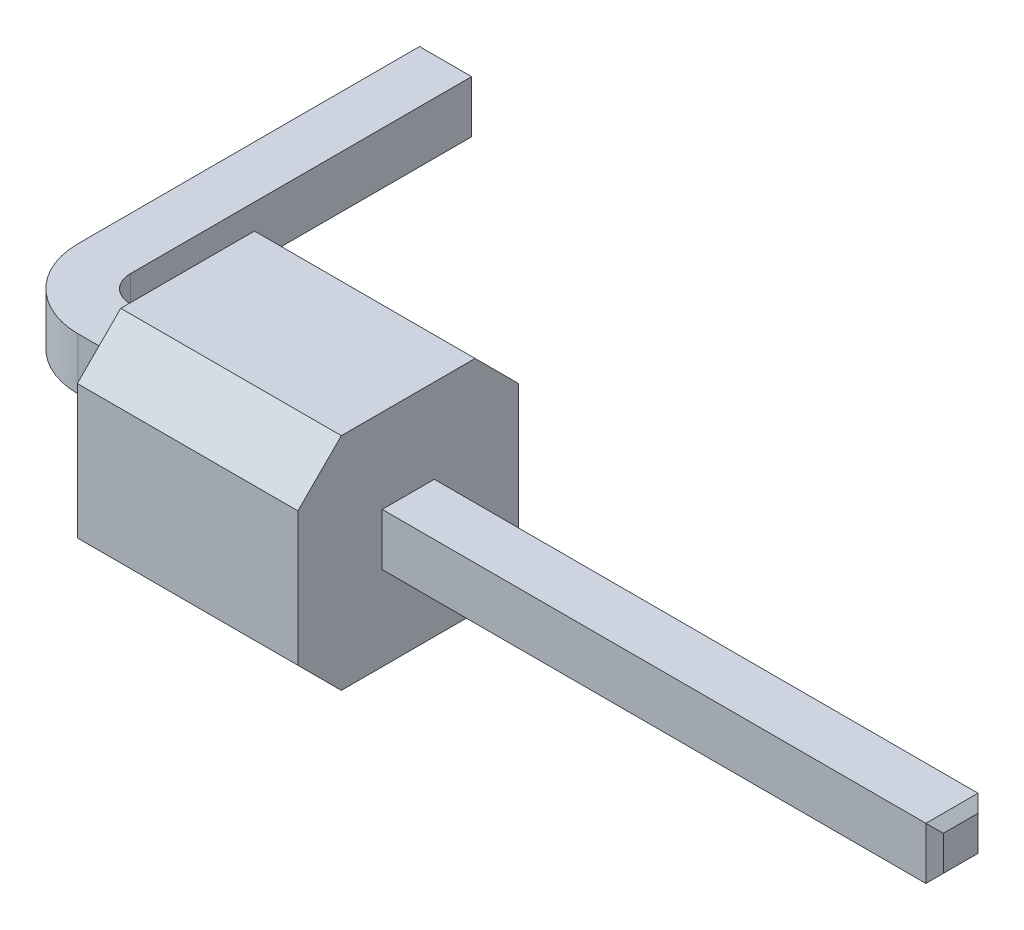
SolidWorks part; units mm, degrees
ref_plane "Front Plane" through (0, 0, 0) normal (0, 0, 1) x (1, 0, 0)
ref_plane "Top Plane" through (0, 0, 0) normal (0, 1, 0) x (1, 0, 0)
ref_plane "Right Plane" through (0, 0, 0) normal (1, 0, 0) x (0, 0, -1)
sketch "Sketch1" plane through (0, 0, 0) normal (1, 0, 0) x (0, 0, -1)
  line L0 (0, 0) -> (-1.27, 0) construction
  line L5 (-1.27, 0) -> (-1.27, 1.27) construction
  line L6 (-2.04, 1.27) -> (-0.5, 1.27)
  line L7 (-0.5, 1.27) -> (0, 0.77)
  line L8 (0, 0.77) -> (0, -0.77)
  line L9 (-2.54, 0.77) -> (-2.54, -0.77)
  line L10 (-2.04, 1.27) -> (-2.54, 0.77)
  line L11 (-0.5, -1.27) -> (0, -0.77)
  line L12 (-2.04, -1.27) -> (-0.5, -1.27)
  line L13 (-2.04, -1.27) -> (-2.54, -0.77)
  point P13 (-2.54, 0)
  dimension "D1" = 1.27
  dimension "D2" = 45
  dimension "D3" = 0.5
extrude "Plastic" add sketch "Sketch1" along normal blind 2.54
sketch "Sketch2" plane through (0, 0, 0) normal (0, 1, 0) x (1, 0, 0)
  line L0 (-1.56, 3.36) -> (-1.56, -0.67) construction
  line L1 (-0.96, -1.27) -> (8.9, -1.27) construction
  line L2 (0, -2.04) -> (0, -0.5) construction
  line L3 (-1.86, 3.36) -> (-1.86, -0.67)
  line L4 (-0.96, -1.57) -> (8.9, -1.57)
  line L5 (-1.26, 3.36) -> (-1.26, -0.67)
  line L6 (-0.96, -0.97) -> (8.9, -0.97)
  line L7 (-1.86, 3.36) -> (-1.26, 3.36)
  line L8 (8.9, -1.57) -> (8.9, -0.97)
  line L9 (2.54, -2.54) -> (0, -2.54) construction
  line L10 (2.54, -2.04) -> (2.54, -0.5) construction
  arc A0 (-1.56, -0.67) -> (-0.96, -1.27) centre (-0.96, -0.67) ccw construction
  arc A1 (-1.86, -0.67) -> (-0.96, -1.57) centre (-0.96, -0.67) ccw
  arc A2 (-1.26, -0.67) -> (-0.96, -0.97) centre (-0.96, -0.67) ccw
  point P5 (0, -1.27)
  dimension "D1" = 0.6
  dimension "D4" = 8.9
  dimension "D5" = 5.9
  dimension "D6" = 4.4
  dimension "D2" = 0.3
  dimension "D3" = 0.3
extrude "Contact" add sketch "Sketch2" along normal mid plane 0.6
chamfer "Chamfer1" distance 0.1 angle 45 8 edges at (8.9, 0.3, 1.27) (8.9, 0, 1.57) (8.9, -0.3, 1.27) (8.9, 0, 0.97) (-1.56, 0.3, -3.36) (-1.26, 0, -3.36) (-1.86, 0, -3.36) (-1.56, -0.3, -3.36)
